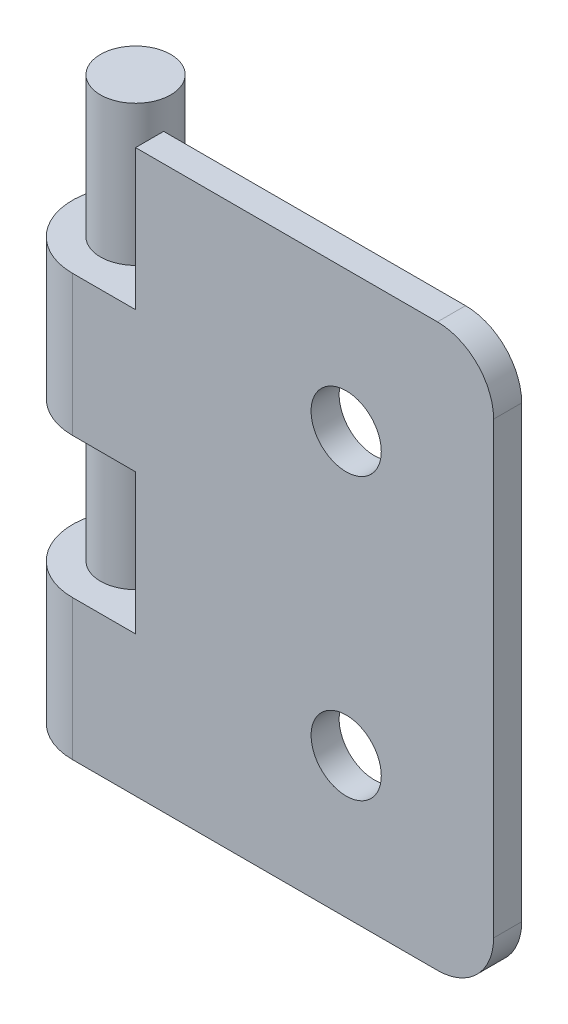
SolidWorks part; units mm, degrees
ref_plane "前视基准面" through (0, 0, 0) normal (0, 0, 1) x (1, 0, 0)
ref_plane "上视基准面" through (0, 0, 0) normal (0, 1, 0) x (1, 0, 0)
ref_plane "右视基准面" through (0, 0, 0) normal (1, 0, 0) x (0, 0, -1)
sketch "草图1" plane through (0, 0, 0) normal (0, 1, 0) x (1, 0, 0)
  line L0 (0, -4.5) -> (30, -4.5)
  line L1 (30, -4.5) -> (30, -2.5)
  line L2 (30, -2.5) -> (3.7417, -2.5)
  circle A0 centre (0, 0) radius 2.5
  arc A1 (3.7417, -2.5) -> (0, -4.5) centre (0, 0) ccw
  dimension "D1" = 9
  dimension "D2" = 5
  dimension "D3" = 2
  dimension "D4" = 30
extrude "凸台-拉伸1" add sketch "草图1" along normal blind 40
sketch "草图2" plane through (0, 0, 4.5) normal (0, 0, 1) x (1, 0, 0)
  line L0 (30, 20) -> (0, 20) construction
  line L1 (30, 40) -> (30, 0) construction
  line L2 (0, 40) -> (0, 0) construction
  circle A0 centre (19.5, 30) radius 2.5
  circle A1 centre (19.5, 10) radius 2.5
  dimension "D1" = 5
  dimension "D2" = 20
  dimension "D3" = 19.5
extrude "切除-拉伸1" cut sketch "草图2" against normal up to next
sketch "草图3" plane through (0, 0, 2.5) normal (0, 0, -1) x (-1, 0, 0)
  line L0 (4.5, 0) -> (4.5, 40) construction
  line L1 (-4.5, 40) -> (4.5, 40)
  line L2 (-4.5, 40) -> (-4.5, 30)
  line L3 (-4.5, 30) -> (4.5, 30)
  line L4 (4.5, 40) -> (4.5, 30)
  line L5 (-4.5, 40) -> (-4.5, 0) construction
  line L6 (-4.5, 20) -> (4.5, 20)
  line L7 (-4.5, 20) -> (-4.5, 10)
  line L8 (-4.5, 10) -> (4.5, 10)
  line L9 (4.5, 20) -> (4.5, 10)
  dimension "D1" = 10
  dimension "D2" = 10
  dimension "D3" = 10
extrude "切除-拉伸2" cut sketch "草图3" against normal mid plane 40
fillet "圆角1" radius 4 2 edges at (30, 40, 3.5) (30, 0, 3.5)
sketch "草图4" plane through (0, 0, 0) normal (0, -1, 0) x (1, 0, 0)
  circle A0 centre (0, 0) radius 2.5
extrude "凸台-拉伸2" add sketch "草图4" against normal blind 40
